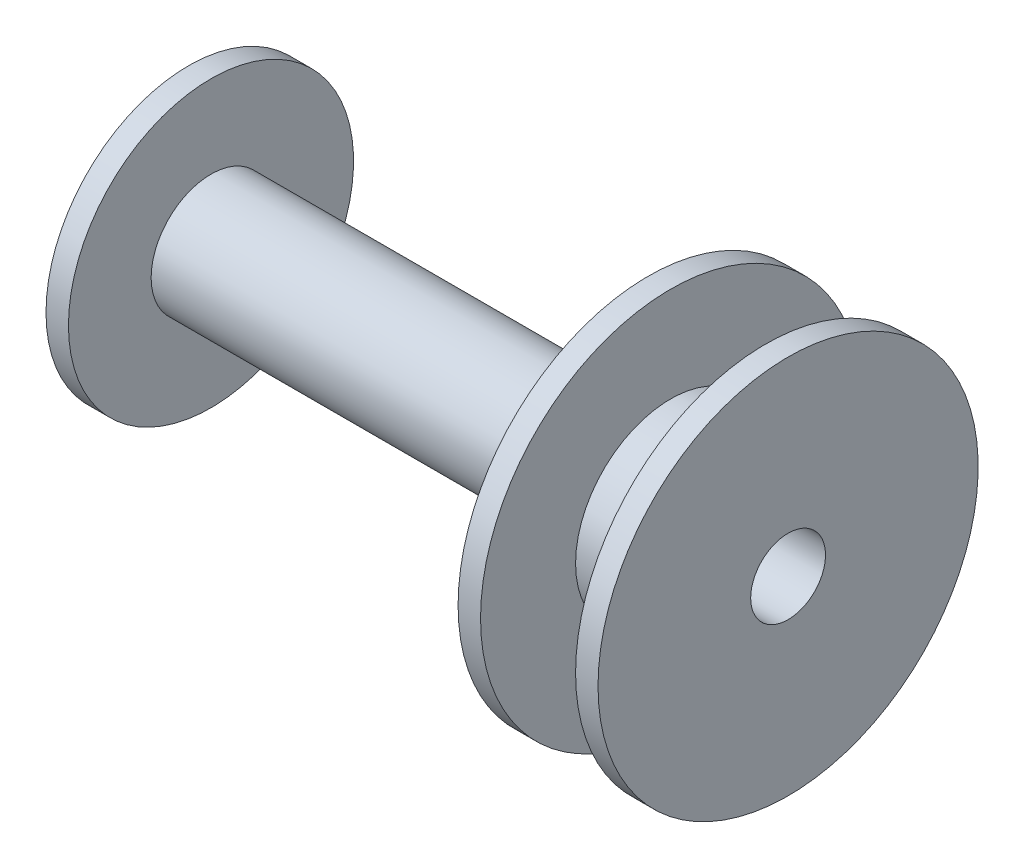
SolidWorks part; units mm, degrees
ref_plane "Front Plane" through (0, 0, 0) normal (0, 0, 1) x (1, 0, 0)
ref_plane "Top Plane" through (0, 0, 0) normal (0, 1, 0) x (1, 0, 0)
ref_plane "Right Plane" through (0, 0, 0) normal (1, 0, 0) x (0, 0, -1)
sketch "Sketch1" plane through (0, 0, 0) normal (0, 0, 1) x (1, 0, 0)
  line L0 (-22.8188, 0) -> (24.3316, 0) construction
  line L1 (-4.8988, 5) -> (-4.8988, 19.05)
  line L2 (-4.8988, 19.05) -> (-1.8988, 19.05)
  line L3 (-1.8988, 19.05) -> (-1.8988, 8)
  line L4 (-1.8988, 8) -> (56.5212, 8)
  line L5 (56.5212, 8) -> (56.5212, 25.4)
  line L6 (56.5212, 25.4) -> (59.5212, 25.4)
  line L7 (59.5212, 25.4) -> (59.5212, 12.7)
  line L8 (59.5212, 12.7) -> (72.2212, 12.7)
  line L9 (72.2212, 12.7) -> (72.2212, 25.4)
  line L10 (72.2212, 25.4) -> (75.2212, 25.4)
  line L11 (75.2212, 25.4) -> (75.2212, 5)
  line L12 (75.2212, 5) -> (-4.8988, 5)
  dimension "D1" = 3
  dimension "D2" = 3
  dimension "D3" = 3
  dimension "D4" = 12.7
  dimension "D5" = 5
  dimension "D6" = 19.05
  dimension "D7" = 3
  dimension "D8" = 58.42
  dimension "D9" = 25.4
  dimension "D10" = 25.4
  dimension "D11" = 12.7
revolve "Revolve1" add sketch "Sketch1" angle 360 about L0
